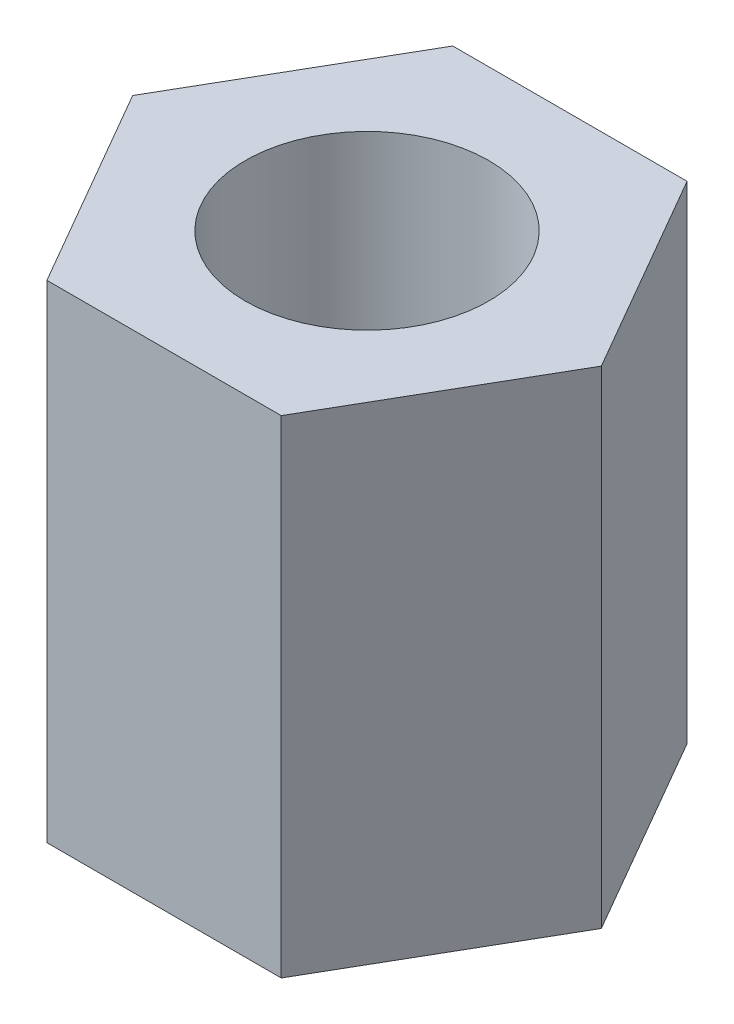
SolidWorks part; units mm, degrees
ref_plane "Front Plane" through (0, 0, 0) normal (0, 0, 1) x (1, 0, 0)
ref_plane "Top Plane" through (0, 0, 0) normal (0, 1, 0) x (1, 0, 0)
ref_plane "Right Plane" through (0, 0, 0) normal (1, 0, 0) x (0, 0, -1)
sketch "Croquis1" plane through (0, 0, 0) normal (0, 1, 0) x (1, 0, 0)
  line L5 (1.4434, -2.5) -> (2.8868, 0)
  line L6 (2.8868, 0) -> (1.4434, 2.5)
  line L7 (1.4434, 2.5) -> (-1.4434, 2.5)
  line L8 (-1.4434, 2.5) -> (-2.8868, 0)
  line L9 (-2.8868, 0) -> (-1.4434, -2.5)
  line L10 (-1.4434, -2.5) -> (1.4434, -2.5)
  circle A0 centre (0, 0) radius 1.5
  circle A1 centre (0, 0) radius 2.5 construction
  point P0 (0, 0)
  dimension "D3" = 3
  dimension "D1" = 5
extrude "Saliente-Extruir1" add sketch "Croquis1" along normal blind 6
